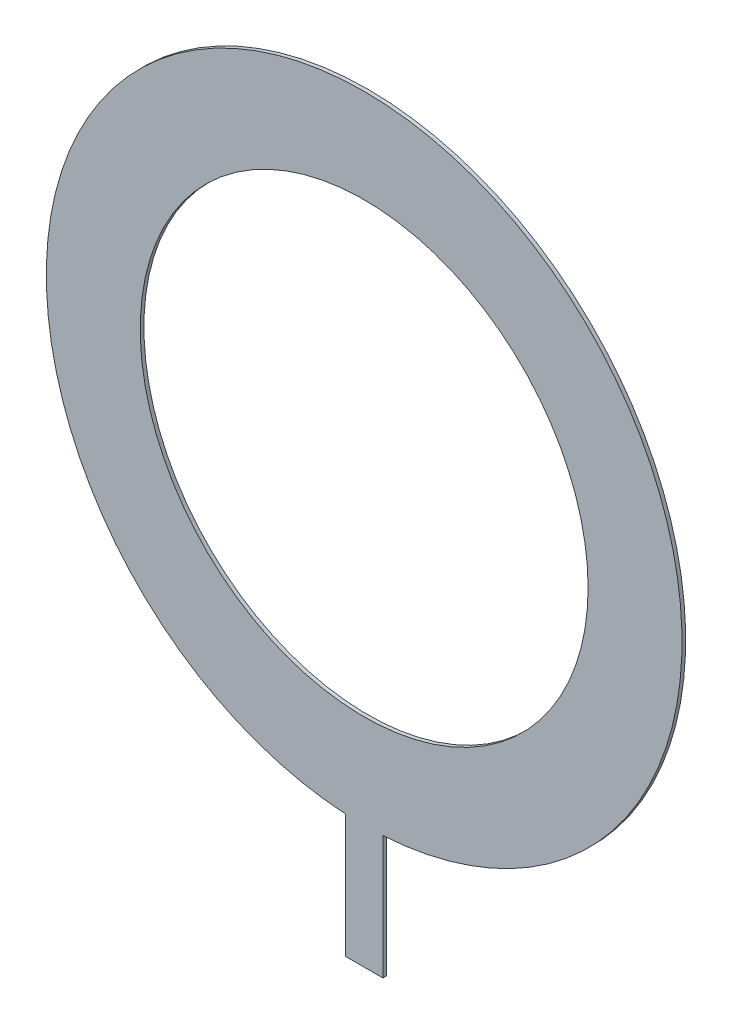
SolidWorks part; units mm, degrees
material "Brass"
ref_plane "Front" through (0, 0, 0) normal (0, 0, 1) x (1, 0, 0)
ref_plane "Top" through (0, 0, 0) normal (0, 1, 0) x (1, 0, 0)
ref_plane "Right" through (0, 0, 0) normal (1, 0, 0) x (0, 0, -1)
sketch "Sketch1" plane through (0, 0, 0) normal (0, 0, 1) x (1, 0, 0)
  line L0 (0, -7.75) -> (0, -15.25)
  line L2 (-0.65, -15.25) -> (0.65, -15.25)
  line L3 (-0.65, -15.25) -> (-0.65, -7.75)
  line L4 (-0.65, -7.75) -> (0.65, -7.75)
  line L5 (0.65, -15.25) -> (0.65, -7.75)
  circle A0 centre (0, 0) radius 11
  circle A1 centre (0, 0) radius 7.75
  point P10 (0, -7.75)
  point P13 (0, -15.25)
  dimension "D1" = 22
  dimension "D2" = 15.5
  dimension "D3" = 1.3
  dimension "D4" = 7.5
extrude "Boss-Extrude1" add sketch "Sketch1" along normal blind 0.127 contours L4 A1 L5 A0 L3 | L0 A0 L5 L4 | L3 A0 L0 L4 | A0 L3 L2 L0 | A0 L0 L2 L5
